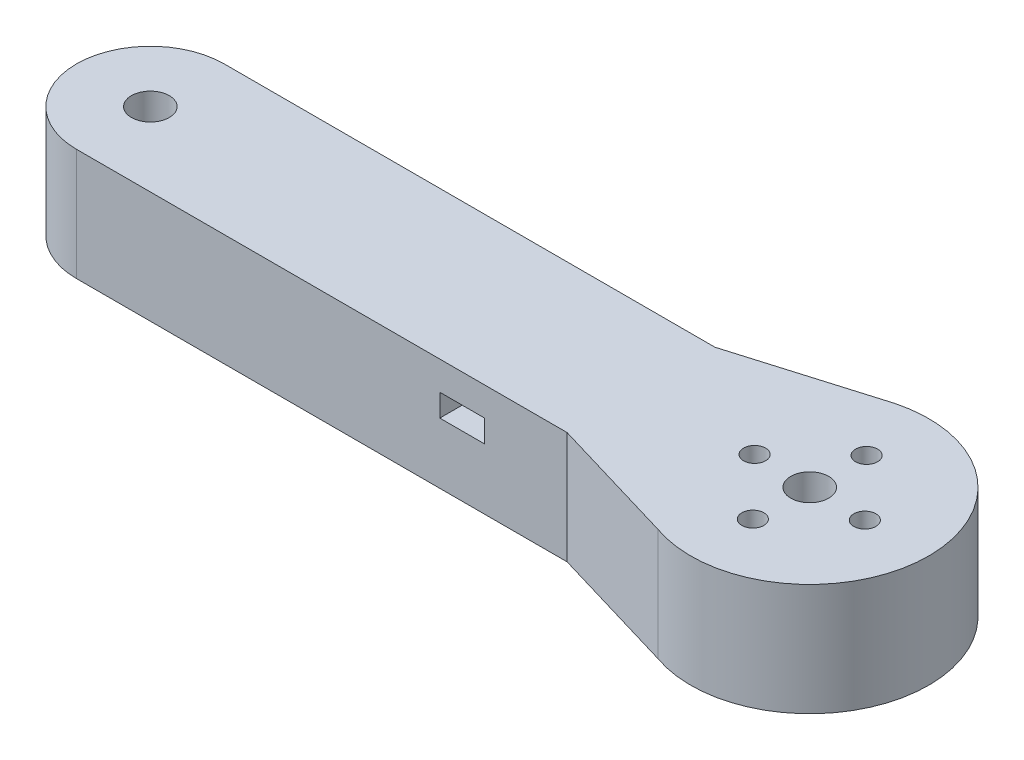
SolidWorks part; units mm, degrees
ref_plane "Front Plane" through (0, 0, 0) normal (0, 0, 1) x (1, 0, 0)
ref_plane "Top Plane" through (0, 0, 0) normal (0, 1, 0) x (1, 0, 0)
ref_plane "Right Plane" through (0, 0, 0) normal (1, 0, 0) x (0, 0, -1)
sketch "Sketch2" plane through (0, 0, 0) normal (0, 1, 0) x (1, 0, 0)
  line L0 (0, 0) -> (74.7776, 0) construction
  line L1 (0, 8.382) -> (74.7776, 8.382)
  line L2 (0, -8.382) -> (74.7776, -8.382)
  arc A0 (0, 8.382) -> (0, -8.382) centre (0, 0) ccw
  arc A1 (74.7776, -8.382) -> (74.7776, 8.382) centre (74.7776, 0) ccw
  circle A2 centre (0, 0) radius 2.15
  circle A3 centre (74.7776, 0) radius 2.15
  point P3 (37.3888, 0)
  dimension "D3" = 4.3
  dimension "D4" = 4.3
  dimension "D1" = 74.7776
  dimension "D2" = 16.764
extrude "Boss-Extrude1" add sketch "Sketch2" against normal blind 12.7 contours L2 A1 L1 A0 | A2 | A3
sketch "Sketch3" plane through (0, 0, -8.382) normal (0, 0, -1) x (-1, 0, 0)
  line L1 (-46.2901, -5.7986) -> (-41.2101, -5.7986)
  line L2 (-46.2901, -5.7986) -> (-46.2901, -3.2586)
  line L3 (-46.2901, -3.2586) -> (-41.2101, -3.2586)
  line L4 (-41.2101, -5.7986) -> (-41.2101, -3.2586)
  dimension "D1" = 2.54
  dimension "D2" = 5.08
extrude "Cut-Extrude1" cut sketch "Sketch3" against normal through all both
sketch "Sketch4" plane through (0, 0, 0) normal (0, 1, 0) x (1, 0, 0)
  line L0 (55.6443, 8.382) -> (71.3773, 13.0648)
  line L1 (0, 8.382) -> (74.7776, 8.382) construction
  line L2 (55.6443, -8.382) -> (70.2806, -12.729)
  line L3 (0, -8.382) -> (74.7776, -8.382) construction
  line L4 (55.6443, -8.382) -> (64.195, -8.382)
  line L5 (55.6443, 8.382) -> (64.195, 8.382)
  circle A0 centre (74.7776, 0) radius 2.15
  circle A1 centre (74.7776, 0) radius 13.5
  line M5 (0, -8.382) -> (74.7776, -8.382)
  arc M6 (74.7776, -8.382) -> (74.7776, 8.382) centre (74.7776, 0) ccw
  line M7 (74.7776, 8.382) -> (0, 8.382)
  dimension "D1" = 27
extrude "Boss-Extrude2" add sketch "Sketch4" against normal up to surface (12.7 mm away) contours L0 A1 M7 M6 M5 | A1 L0 M7 | A1 L2 M5 up to face at (74.7776, -12.7, 2.15)
sketch "Sketch5" plane through (0, -12.7, 0) normal (0, -1, 0) x (-1, 0, 0)
  circle A0 centre (-74.7776, 0) radius 9.75
  dimension "D1" = 19.5
extrude "Cut-Extrude2" cut sketch "Sketch5" against normal blind 5.5
ref_plane "Plane1" through (0, -6.35, 0) normal (0, -1, 0) x (-1, 0, 0)
sketch "Sketch6" plane through (0, -7.2, 0) normal (0, -1, 0) x (-1, 0, 0)
  circle A0 centre (-74.8769, 6.35) radius 1.25
  circle A1 centre (-68.4276, 0.0993) radius 1.25
  circle A2 centre (-74.6783, -6.35) radius 1.25
  circle A3 centre (-81.1276, -0.0993) radius 1.25
  point P2 (-74.7776, 0)
  point P5 (0, 0)
  point P6 (0, -74.7776)
  point P15 (-74.7776, 0)
  dimension "D1" = 2.5
  dimension "D2" = 6.35
  dimension "D3" = 4
extrude "Cut-Extrude3" cut sketch "Sketch6" against normal through all both and the other way through all
